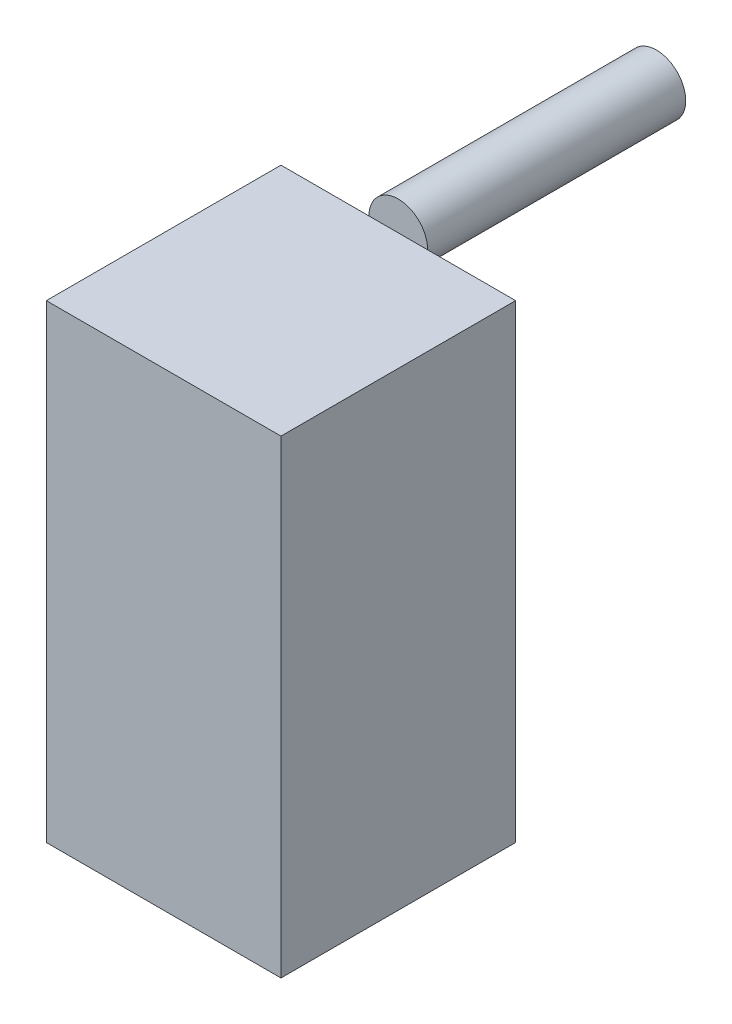
SolidWorks part; units mm, degrees
ref_plane "Front Plane" through (0, 0, 0) normal (0, 0, 1) x (1, 0, 0)
ref_plane "Top Plane" through (0, 0, 0) normal (0, 1, 0) x (1, 0, 0)
ref_plane "Right Plane" through (0, 0, 0) normal (1, 0, 0) x (0, 0, -1)
sketch "Sketch1" plane through (0, 0, 0) normal (0, 1, 0) x (1, 0, 0)
  line L1 (-10, 10) -> (10, 10)
  line L2 (-10, 10) -> (-10, -10)
  line L3 (-10, -10) -> (10, -10)
  line L4 (10, 10) -> (10, -10)
  line L5 (-10, 10) -> (10, -10) construction
  line L6 (-10, -10) -> (10, 10) construction
  point P0 (0, 0)
  dimension "D1" = 20
  dimension "D2" = 20
extrude "Boss-Extrude1" add sketch "Sketch1" along normal blind 40
sketch "Sketch3" plane through (0, 0, -10) normal (0, 0, -1) x (-1, 0, 0)
  line L0 (-10, 40) -> (10, 40) construction
  circle A0 centre (0, 40) radius 2.5
  dimension "D1" = 5
extrude "Boss-Extrude3" add sketch "Sketch3" along normal blind 22
